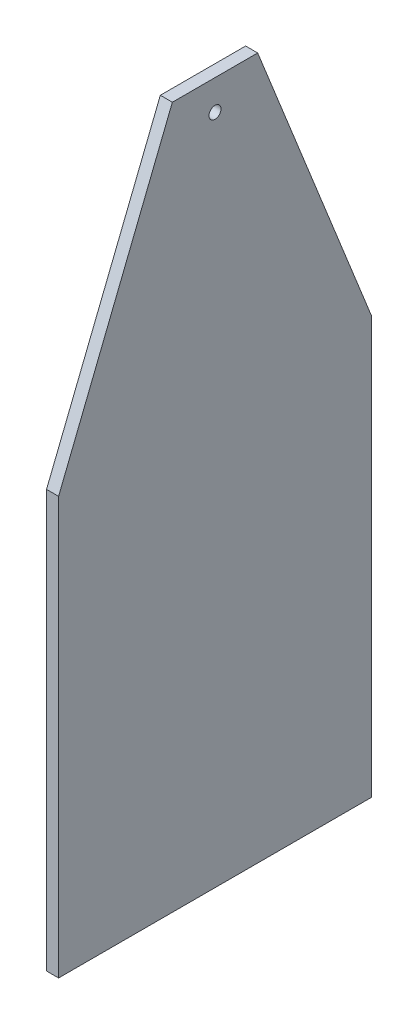
SolidWorks part; units mm, degrees
ref_plane "Front Plane" through (0, 0, 0) normal (0, 0, 1) x (1, 0, 0)
ref_plane "Top Plane" through (0, 0, 0) normal (0, 1, 0) x (1, 0, 0)
ref_plane "Right Plane" through (0, 0, 0) normal (1, 0, 0) x (0, 0, -1)
sketch "Sketch1" plane through (0, 0, 0) normal (0, 1, 0) x (1, 0, 0)
  line L1 (0, 82.5) -> (6.35, 82.5)
  line L2 (0, 82.5) -> (0, -82.5)
  line L3 (0, -82.5) -> (6.35, -82.5)
  line L4 (6.35, 82.5) -> (6.35, -82.5)
  dimension "D1" = 6.35
  dimension "D2" = 165
extrude "Boss-Extrude1" add sketch "Sketch1" along normal blind 370
hole_wizard "1/4 (0.25) Diameter Hole1" positions "Sketch3" profile "Sketch2" hole size "1/4" standard "ANSI Inch" end condition through all
sketch "Sketch3" plane through (6.35, 0, 0) normal (1, 0, 0) x (0, 0, -1)
  point P0 (0, 354.1473)
sketch "Sketch2" plane through (6.35, 354.1473, 0) normal (0, 1, 0) x (0, 0, -1)
  line L0 (0, 0) -> (0, 6.35)
  line L1 (0, 6.35) -> (3.175, 6.35)
  line L2 (3.175, 6.35) -> (3.175, 0)
  line L5 (3.175, 0) -> (0, 0)
  line L11 (0, -6.35) -> (0, 107.95) construction
  dimension "Thru Hole Dia." = 6.35
  dimension "Thru Hole Depth" = 6.35
sketch "Sketch4" plane through (6.35, 0, 0) normal (1, 0, 0) x (0, 0, -1)
  line L0 (-22.5, 370) -> (-82.5, 220)
  line L1 (-82.5, 370) -> (82.5, 370) construction
  line L2 (-82.5, 370) -> (-82.5, 0) construction
  line L3 (-82.5, 220) -> (-82.5, 370)
  line L4 (-82.5, 370) -> (-22.5, 370)
  line L5 (0, 370) -> (0, 0) construction
  line L6 (82.5, 370) -> (22.5, 370)
  line L7 (82.5, 220) -> (82.5, 370)
  line L8 (22.5, 370) -> (82.5, 220)
  dimension "D1" = 60
  dimension "D2" = 150
extrude "Cut-Extrude1" cut sketch "Sketch4" against normal through all
